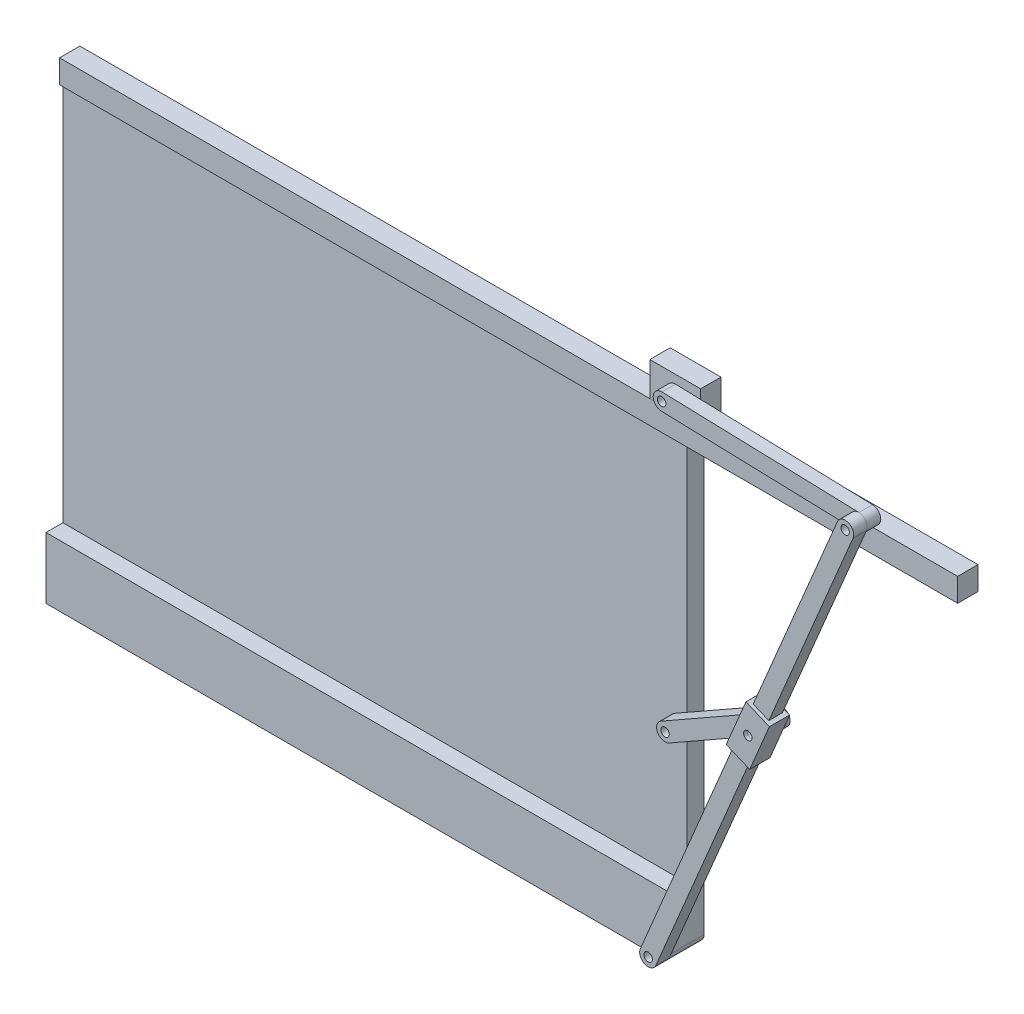
SolidWorks part; units mm, degrees
ref_plane "Front Plane" through (0, 0, 0) normal (0, 0, 1) x (1, 0, 0)
ref_plane "Top Plane" through (0, 0, 0) normal (0, 1, 0) x (1, 0, 0)
ref_plane "Right Plane" through (0, 0, 0) normal (1, 0, 0) x (0, 0, -1)
sketch "Sketch1" plane through (0, 0, 0) normal (0, 0, 1) x (1, 0, 0)
  line L0 (0, 0) -> (116.348, 276.5197)
  line L1 (0, 110) -> (60.8456, 144.6094)
  line L2 (0, 280) -> (116.348, 276.5197)
  line L3 (0, 280) -> (-50000, 280) construction
  line L4 (-15, 270) -> (15, 270)
  line L5 (-15, 270) -> (-15, 290)
  line L6 (-15, 290) -> (15, 290)
  line L7 (15, 270) -> (15, 290)
  line L8 (-15, 270) -> (15, 290) construction
  line L9 (-15, 290) -> (15, 270) construction
  line L10 (0, 0) -> (-50000, 0) construction
  line L11 (48.1152, 133.6921) -> (61.9412, 127.8747)
  line L12 (48.1152, 133.6921) -> (59.75, 161.3441)
  line L13 (61.9412, 127.8747) -> (73.576, 155.5267)
  line L14 (59.75, 161.3441) -> (73.576, 155.5267)
  line L15 (48.1152, 133.6921) -> (73.576, 155.5267) construction
  line L16 (61.9412, 127.8747) -> (59.75, 161.3441) construction
  point P10 (0, 0)
  dimension "D1" = 70
  dimension "D2" = 300
  dimension "D3" = 280
  dimension "D4" = 110
  dimension "D5" = 116.4
  dimension "D6" = 30
  dimension "D7" = 20
  dimension "D8" = 15
  dimension "D9" = 30
sketch "Sketch3" plane through (0, 0, 0) normal (0, 0, 1) x (1, 0, 0)
  line L0 (0, 110) -> (60.8456, 144.6094) construction
  line L1 (-2.4721, 114.3461) -> (58.3735, 148.9555)
  line L2 (2.4721, 105.6539) -> (63.3177, 140.2633)
  arc A0 (-2.4721, 114.3461) -> (2.4721, 105.6539) centre (0, 110) ccw
  arc A1 (63.3177, 140.2633) -> (58.3735, 148.9555) centre (60.8456, 144.6094) ccw
  point P4 (30.4228, 127.3047)
  dimension "D1" = 5
extrude "Boss-Extrude2" add sketch "Sketch3" along normal blind 8
sketch "Sketch5" plane through (0, 0, 8) normal (0, 0, 1) x (1, 0, 0)
  line L0 (59.75, 161.3441) -> (73.576, 155.5267)
  line L1 (59.75, 161.3441) -> (48.1152, 133.6921)
  line L2 (73.576, 155.5267) -> (61.9412, 127.8747)
  line L3 (48.1152, 133.6921) -> (61.9412, 127.8747)
  line L4 (48.1152, 133.6921) -> (61.9412, 127.8747) construction
extrude "Boss-Extrude5" add sketch "Sketch5" along normal blind 12 separate body
sketch "Sketch6" plane through (66.663, 158.4354, 0) normal (0.3878, 0.9217, 0) x (0.9217, -0.3878, 0)
  line L0 (-7.5, -20) -> (7.5, -20)
  line L1 (-7.5, -20) -> (-7.5, -8.002)
  line L2 (7.5, -20) -> (7.5, -8.002)
  line L3 (-7.5, -8.002) -> (7.5, -8.002)
  line L5 (-5, -18) -> (5, -18)
  line L6 (-5, -18) -> (-5, -10.002)
  line L7 (-5, -10.002) -> (5, -10.002)
  line L8 (5, -18) -> (5, -10.002)
  dimension "D1" = 2
  dimension "D2" = 2
  dimension "D3" = 2.5
  dimension "D4" = 2.5
extrude "Cut-Extrude1" cut sketch "Sketch6" against normal blind 35 contours L5 L8 L7 L6
sketch "Sketch8" plane through (0, 0, 10.002) normal (0, 0, 1) x (1, 0, 0)
  line L0 (0, 0) -> (116.348, 276.5197) construction
  line L1 (-4.6087, 1.9391) -> (111.7393, 278.4588)
  line L2 (4.6087, -1.9391) -> (120.9566, 274.5806)
  arc A0 (-4.6087, 1.9391) -> (4.6087, -1.9391) centre (0, 0) ccw
  arc A1 (120.9566, 274.5806) -> (111.7393, 278.4588) centre (116.348, 276.5197) ccw
  point P4 (58.174, 138.2599)
  dimension "D1" = 5
extrude "Boss-Extrude6" add sketch "Sketch8" along normal blind 8 separate body
sketch "Sketch9" plane through (0, 0, 10.002) normal (0, 0, -1) x (-1, 0, 0)
  line L0 (-116.348, 276.5197) -> (0, 280) construction
  line L1 (-116.4975, 281.5175) -> (-0.1495, 284.9978)
  line L2 (-116.1985, 271.5219) -> (0.1495, 275.0022)
  arc A0 (-116.4975, 281.5175) -> (-116.1985, 271.5219) centre (-116.348, 276.5197) ccw
  arc A1 (0.1495, 275.0022) -> (-0.1495, 284.9978) centre (0, 280) ccw
  point P4 (-58.174, 278.2599)
  dimension "D1" = 5
extrude "Boss-Extrude7" add sketch "Sketch9" along normal blind 8 separate body
sketch "Sketch10" plane through (0, 0, 2.002) normal (0, 0, -1) x (-1, 0, 0)
  line L1 (-15, 290) -> (15, 290)
  line L2 (-15, 290) -> (-15, 270)
  line L3 (-15, 270) -> (15, 270)
  line L4 (15, 290) -> (15, 270)
extrude "Boss-Extrude9" add sketch "Sketch10" along normal blind 12 separate body
sketch "Sketch16" plane through (0, 0, 0) normal (0, 0, 1) x (1, 0, 0)
  line L0 (61.9412, 127.8747) -> (59.75, 161.3441) construction
  circle A0 centre (0, 280) radius 2.5
  circle A1 centre (116.348, 276.5197) radius 2.5
  circle A2 centre (0, 110) radius 2.5
  circle A3 centre (0, 0) radius 2.5
  circle A4 centre (60.8456, 144.6094) radius 2.5
  dimension "D1" = 5
extrude "Cut-Extrude5" cut sketch "Sketch16" against normal through all both and the other way through all
sketch "Sketch12" plane through (0, 0, 0) normal (0, 0, 1) x (1, 0, 0)
  line L0 (166.7565, 270) -> (-363.5021, 270)
  line L1 (-363.5021, 270) -> (-363.5021, -5)
  line L2 (0, -5) -> (-363.5021, -5)
  line L3 (166.7565, 270) -> (166.7565, 256.2121)
  line L5 (5, 256.2121) -> (166.7565, 256.2121)
  line L6 (5, 256.2121) -> (5, 0)
  arc A2 (-4.6087, 1.9391) -> (4.6087, -1.9391) centre (0, 0) ccw construction
  arc A4 (0, -5) -> (5, 0) centre (0, 0) ccw
extrude "Boss-Extrude10" add sketch "Sketch12" against normal blind 10 separate body
sketch "Sketch14" plane through (0, 0, 0) normal (0, 0, 1) x (1, 0, 0)
  line L0 (-363.5021, 270) -> (-363.5021, -5) construction
  line L1 (-363.5021, 256.2121) -> (166.7565, 256.2121)
  line L2 (-363.5021, 256.2121) -> (-363.5021, 270)
  line L3 (-363.5021, 270) -> (166.7565, 270)
  line L4 (166.7565, 256.2121) -> (166.7565, 270)
extrude "Boss-Extrude11" add sketch "Sketch14" along normal blind 2
sketch "Sketch15" plane through (0, 0, 0) normal (0, 0, 1) x (1, 0, 0)
  line L0 (-363.5021, 31.2917) -> (5, 31.2917)
  line L1 (-363.5021, 256.2121) -> (-363.5021, -5) construction
  line L2 (5, 0) -> (5, 256.2121) construction
  line L3 (5, 31.2917) -> (5, 0)
  line L4 (0, -5) -> (-363.5021, -5)
  line L5 (-363.5021, -5) -> (-363.5021, 31.2917)
  arc A0 (0, -5) -> (5, 0) centre (0, 0) ccw
extrude "Boss-Extrude12" add sketch "Sketch15" along normal blind 10
sketch "Sketch11" plane through (0, 0, 0) normal (0, 0, 1) x (1, 0, 0)
  line L0 (61.9412, 127.8747) -> (59.75, 161.3441) construction
  circle A0 centre (0, 280) radius 2.5
  circle A1 centre (116.348, 276.5197) radius 2.5
  circle A2 centre (60.8456, 144.6094) radius 2.5
  circle A3 centre (0, 110) radius 2.5
  circle A4 centre (0, 0) radius 2.5
  dimension "D1" = 5
extrude "Cut-Extrude2" cut sketch "Sketch11" against normal through all and the other way through all
